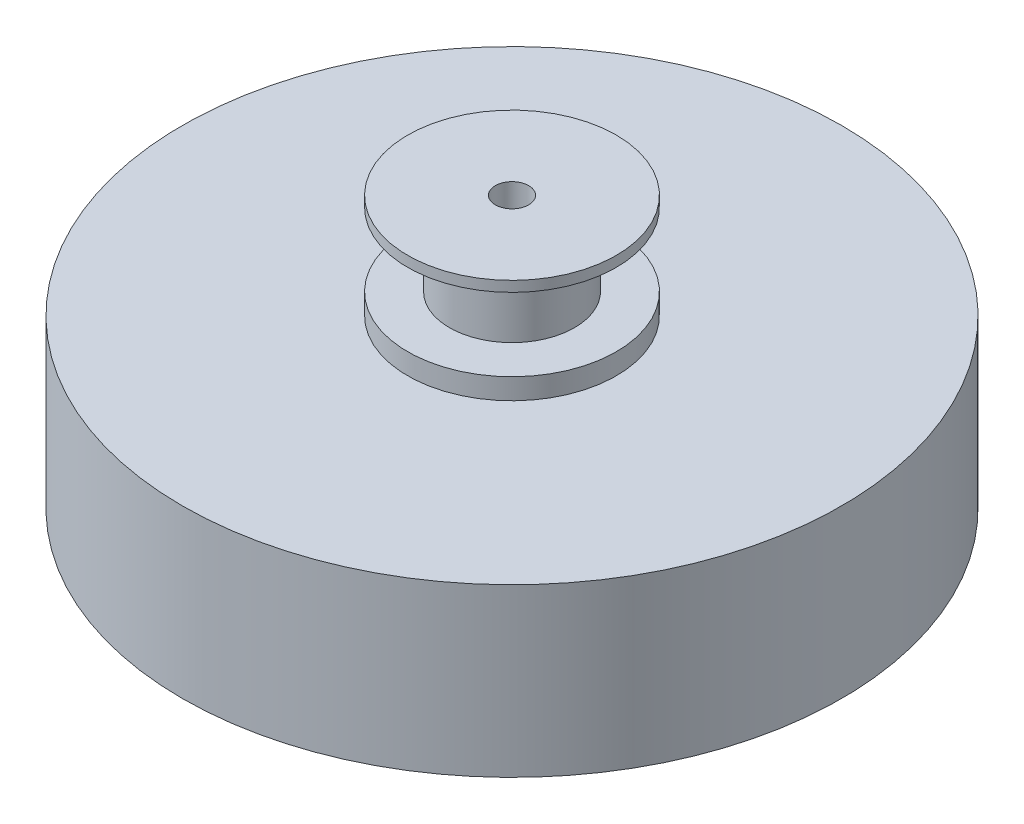
SolidWorks part; units mm, degrees
material "2024-T4"
ref_plane "Front Plane" through (0, 0, 0) normal (0, 0, 1) x (1, 0, 0)
ref_plane "Top Plane" through (0, 0, 0) normal (0, 1, 0) x (1, 0, 0)
ref_plane "Right Plane" through (0, 0, 0) normal (1, 0, 0) x (0, 0, -1)
sketch "Sketch1" plane through (0, 0, 0) normal (1, 0, 0) x (0, 0, -1)
  line L0 (0, -5577.8392) -> (0, 273314.1184) construction
  line L7 (-50, 40) -> (-158, 40)
  line L13 (-30, 85) -> (-50, 85)
  line L14 (-50, 85) -> (-50, 90)
  line L15 (-50, 90) -> (-8, 90)
  line L16 (-50, 40) -> (-50, 50)
  line L17 (-50, 50) -> (-30, 50)
  line L18 (-30, 50) -> (-30, 85)
  line L26 (0, 0) -> (-240.4249, 0) construction
  line L27 (-50, -40) -> (-50, -50)
  line L28 (-50, -50) -> (-30, -50)
  line L29 (-30, -50) -> (-30, -85)
  line L30 (-30, -85) -> (-50, -85)
  line L31 (-50, -85) -> (-50, -90)
  line L32 (-50, -90) -> (-8, -90)
  line L33 (-158, 40) -> (-158, -40)
  line L34 (-158, -40) -> (-50, -40)
  line L35 (-8, -90) -> (-8, 90)
  point P12 (-158, 0)
  dimension "D1" = 80
  dimension "D2" = 158
  dimension "D3" = 30
  dimension "D4" = 50
  dimension "D5" = 100
  dimension "D6" = 170
  dimension "D7" = 180
revolve "Revolve1" add sketch "Sketch1" angle 360 about L0
